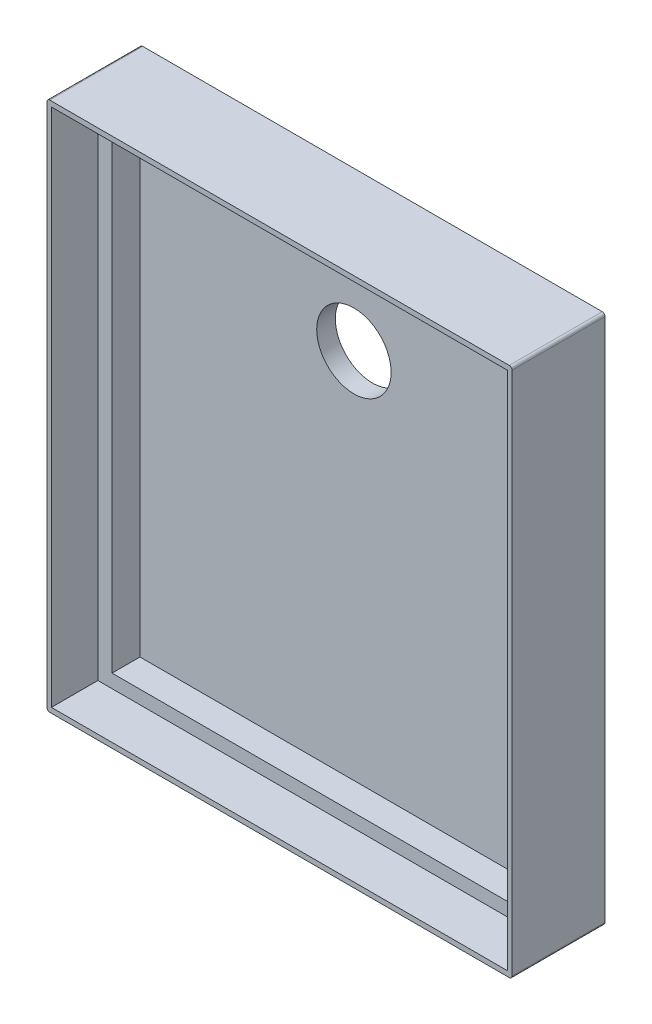
SolidWorks part; units mm, degrees
ref_plane "Front" through (0, 0, 0) normal (0, 0, 1) x (1, 0, 0)
ref_plane "Top" through (0, 0, 0) normal (0, 1, 0) x (1, 0, 0)
ref_plane "Right" through (0, 0, 0) normal (1, 0, 0) x (0, 0, -1)
sketch "草图1" plane through (0, 0, 0) normal (0, 0, 1) x (1, 0, 0)
  line L1 (3, 0) -> (497, 0)
  line L2 (0, -3) -> (0, -567)
  line L3 (3, -570) -> (497, -570)
  line L4 (500, -3) -> (500, -567)
  arc A0 (497, -570) -> (500, -567) centre (497, -567) ccw
  arc A1 (3, -570) -> (0, -567) centre (3, -567) cw
  arc A2 (497, 0) -> (500, -3) centre (497, -3) cw
  arc A3 (0, -3) -> (3, 0) centre (3, -3) cw
  point P7 (500, -570)
  point P12 (500, 0)
  point P15 (0, 0)
  dimension "D3" = 3
  dimension "D1" = 500
  dimension "D2" = 570
extrude "凸台-拉伸1" add sketch "草图1" along normal blind 100
shell "抽壳1" thickness 20
sketch "草图2" plane through (0, 0, 100) normal (0, 0, 1) x (1, 0, 0)
  line L0 (250, -285) -> (99.7674, -285) construction
  line L1 (480, -20) -> (20, -20) construction
  line L2 (250, -20) -> (250, -550) construction
  line L3 (20, -550) -> (480, -550) construction
  line L4 (250, -285) -> (250, -5.49)
  line L5 (4.785, -5.49) -> (495.215, -5.49)
  line L6 (495.215, -5.49) -> (495.215, -20)
  line L7 (4.785, -564.51) -> (495.215, -564.51)
  line L8 (495.215, -564.51) -> (495.215, -550)
  line L9 (495.215, -20) -> (495.215, -550)
  line L10 (4.785, -564.51) -> (4.785, -550)
  line L11 (4.785, -5.49) -> (4.785, -20)
  line L12 (4.785, -20) -> (4.785, -550)
  point P15 (250, -564.51)
extrude "切除-拉伸1" cut sketch "草图2" against normal blind 50
sketch "草图3" plane through (0, 0, 0) normal (0, 0, -1) x (-1, 0, 0)
  line L0 (-250, 0) -> (-250, -150) construction
  line L1 (-497, 0) -> (-3, 0) construction
  circle A0 centre (-250, -150) radius 60
extrude "切除-拉伸2" cut sketch "草图3" against normal blind 50
sketch "草图5" plane through (0, 0, 0) normal (0, 0, -1) x (-1, 0, 0)
  circle A0 centre (-250, -150) radius 60 construction
  circle A1 centre (-250, -150) radius 60
  circle A2 centre (-250, -150) radius 40
  dimension "D1" = 20
extrude "凸台-拉伸2" add sketch "草图5" against normal up to surface (20 mm away) up to face at (310, -150, 20)
